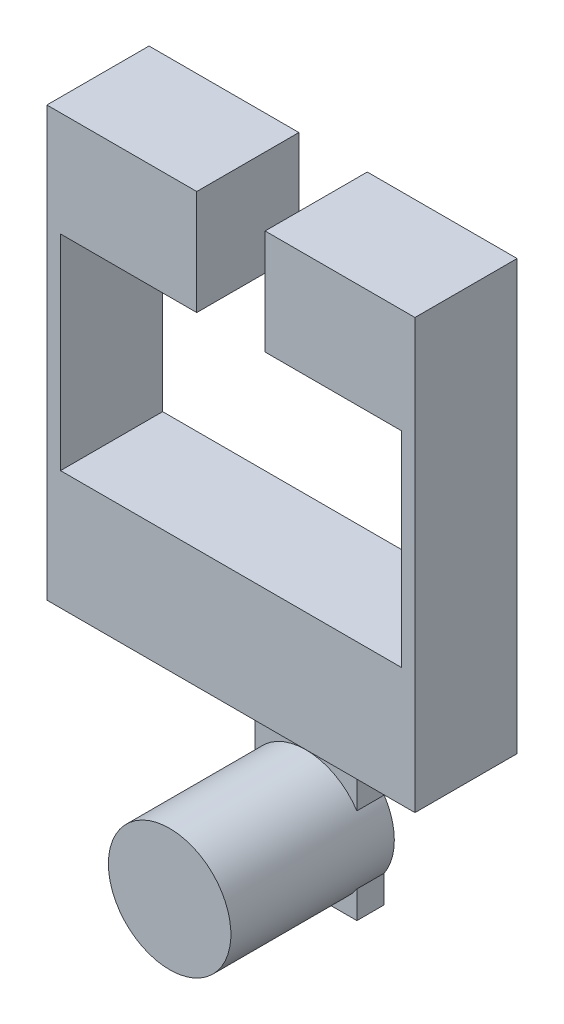
SolidWorks part; units mm, degrees
material "FEA Aluminum"
ref_plane "Front Plane" through (0, 0, 0) normal (0, 0, 1) x (1, 0, 0)
ref_plane "Top Plane" through (0, 0, 0) normal (0, 1, 0) x (1, 0, 0)
ref_plane "Right Plane" through (0, 0, 0) normal (1, 0, 0) x (0, 0, -1)
sketch "Sketch1" plane through (0, 0, 0) normal (0, 0, 1) x (1, 0, 0)
  line L1 (-34.3205, 79.975) -> (34.3205, 79.975)
  line L2 (-34.3205, 79.975) -> (-34.3205, 0)
  line L3 (-34.3205, 0) -> (34.3205, 0)
  line L4 (34.3205, 79.975) -> (34.3205, 0)
  dimension "D1" = 68.641
  dimension "D2" = 79.975
extrude "Main-Body" add sketch "Sketch1" along normal mid plane 19.05
sketch "Sketch2" plane through (0, 0, 9.525) normal (0, 0, 1) x (1, 0, 0)
  line L0 (0, 84.5954) -> (0, -7.8995) construction
  line L1 (-34.3205, 0) -> (34.3205, 0) construction
  line L2 (-31.7805, 60.417) -> (31.7805, 60.417)
  line L3 (-31.7805, 60.417) -> (-31.7805, 22.19)
  line L4 (-31.7805, 22.19) -> (31.7805, 22.19)
  line L5 (31.7805, 60.417) -> (31.7805, 22.19)
  dimension "D1" = 63.561
  dimension "D2" = 38.227
  dimension "D3" = 22.19
extrude "Lower-T-Cavity" cut sketch "Sketch2" against normal through all
sketch "Sketch3" plane through (0, 0, 9.525) normal (0, 0, 1) x (1, 0, 0)
  line L0 (0, 84.1431) -> (0, -5.638) construction
  line L1 (31.7805, 60.417) -> (-31.7805, 60.417) construction
  line L2 (-6.3754, 79.975) -> (6.3754, 79.975)
  line L3 (-6.3754, 79.975) -> (-6.3754, 60.417)
  line L4 (-6.3754, 60.417) -> (6.3754, 60.417)
  line L5 (6.3754, 79.975) -> (6.3754, 60.417)
  line L6 (34.3205, 79.975) -> (-34.3205, 79.975) construction
  dimension "D1" = 12.7508
extrude "Top-Slot" cut sketch "Sketch3" against normal through all
sketch "Sketch4" plane through (0, 0, -9.525) normal (0, 0, -1) x (-1, 0, 0)
  line L0 (0, 84.5954) -> (0, -5.9773) construction
  line L1 (34.3205, 0) -> (-34.3205, 0) construction
  line L2 (-9.525, 0) -> (9.525, 0)
  line L3 (-9.525, 0) -> (-9.525, -36.8237)
  line L4 (-9.525, -36.8237) -> (9.525, -36.8236)
  line L5 (9.525, 0) -> (9.525, -36.8236)
  dimension "D1" = 19.05
  dimension "D2" = 36.8236
extrude "Hanger" add sketch "Sketch4" against normal blind 5.08
sketch "Sketch5" plane through (0, 0, -9.525) normal (0, 0, -1) x (-1, 0, 0)
  circle A0 centre (0, -25.4) radius 11.4236
  dimension "D2" = 22.8473
  dimension "D1" = 25.4
extrude "Strap-Pin" add sketch "Sketch5" against normal blind 30.48
equation "\"Bracket_depth\"= 0.750in"
equation "\"Pin_diameter\"= 0.8995in"
equation "\"Pin_free_length\"= 1.000in"
equation "\"Hanger_width\"= 0.750in"
equation "\"Hanger_thickness\"= 0.2000in"
equation "\"Hanger_length\"= 1.000in"
equation "\"Web_thickness\"= 0.100in"
equation "\"Lip_height\"= 0.770in"
equation "\"Top_slot_width\"= 0.5020in"
equation "\"T_cavity_width\"= 2.5024in"
equation "\"T_cavity_height\"= 1.5050in"
equation "\"Crossmember_height\"= ( 3 * 1400 * 2.6024 / ( 2 * 0.75 * 10000 ) ) ^ ( 1 / 2 ) * 1in + 0.020in"
equation "\"D1@Sketch1\"=\"T_cavity_width\"+2*\"Web_thickness\""
equation "\"D2@Sketch1\"=\"Crossmember_height\"+\"T_cavity_height\"+\"Lip_height\""
equation "\"D1@Main-Body\" = \"Bracket_depth\""
equation "\"D1@Sketch2\"=\"T_cavity_width\""
equation "\"D2@Sketch2\"=\"T_cavity_height\""
equation "\"D3@Sketch2\"=\"Crossmember_height\""
equation "\"D1@Sketch3\"=\"Top_slot_width\""
equation "\"D1@Sketch4\"=\"Hanger_width\""
equation "\"D2@Sketch4\"=\"Hanger_length\"+\"Pin_diameter\"/2"
equation "\"D1@Hanger\" = \"Hanger_thickness\""
equation "\"D1@Sketch5\"=\"Hanger_length\""
equation "\"D2@Sketch5\"=\"Pin_diameter\""
equation "\"D1@Strap-Pin\" = \"Pin_free_length\" + \"Hanger_thickness\""
